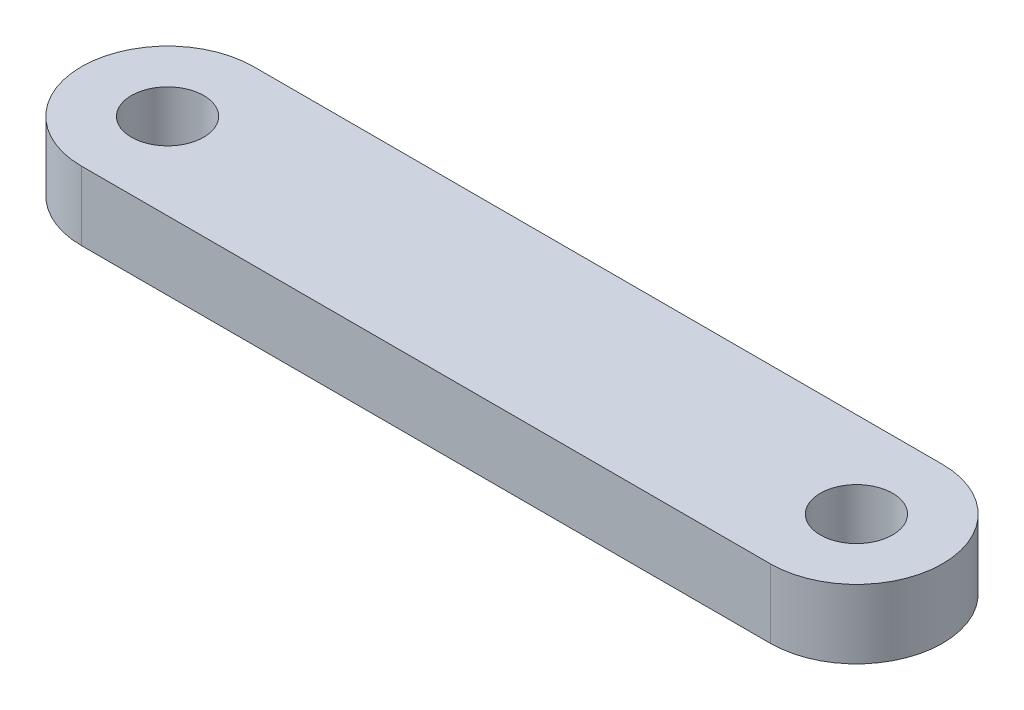
SolidWorks part; units mm, degrees
ref_plane "Front Plane" through (0, 0, 0) normal (0, 0, 1) x (1, 0, 0)
ref_plane "Top Plane" through (0, 0, 0) normal (0, 1, 0) x (1, 0, 0)
ref_plane "Right Plane" through (0, 0, 0) normal (1, 0, 0) x (0, 0, -1)
sketch "Sketch1" plane through (0, 0, 0) normal (0, 1, 0) x (1, 0, 0)
  line L0 (0, 0) -> (20, 0) construction
  line L1 (0, 2.5) -> (20, 2.5)
  line L2 (0, -2.5) -> (20, -2.5)
  arc A0 (0, 2.5) -> (0, -2.5) centre (0, 0) ccw
  arc A1 (20, -2.5) -> (20, 2.5) centre (20, 0) ccw
  circle A2 centre (0, 0) radius 1.05
  circle A3 centre (20, 0) radius 1.05
  point P3 (10, 0)
  dimension "D2" = 2.5
  dimension "D4" = 2.1
  dimension "D5" = 2.1
  dimension "D1" = 20
extrude "Boss-Extrude1" add sketch "Sketch1" along normal blind 2
